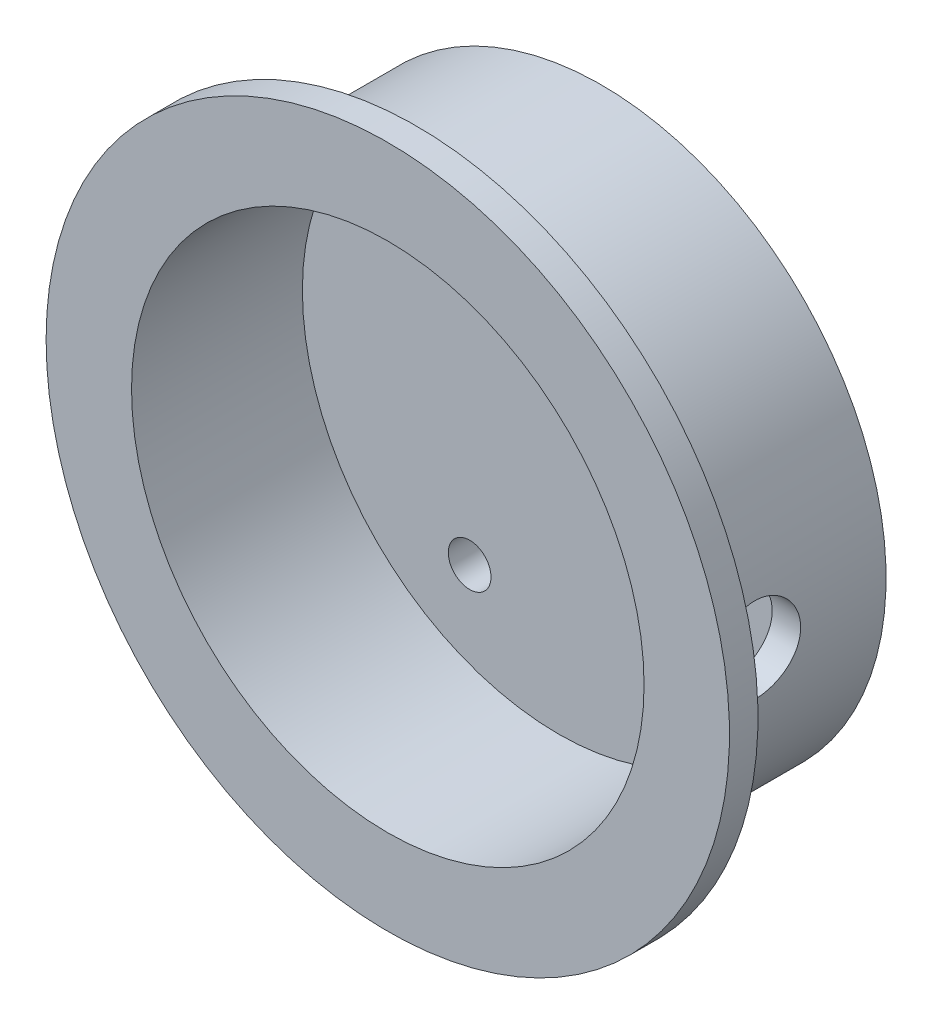
SolidWorks part; units mm, degrees
ref_plane "前视基准面" through (0, 0, 0) normal (0, 0, 1) x (1, 0, 0)
ref_plane "上视基准面" through (0, 0, 0) normal (0, 1, 0) x (1, 0, 0)
ref_plane "右视基准面" through (0, 0, 0) normal (1, 0, 0) x (0, 0, -1)
sketch "草图2" plane through (0, 0, 0) normal (0, 1, 0) x (1, 0, 0)
  line L0 (0, 0) -> (0, -1) construction
  line L1 (0, 0) -> (40, 0)
  line L2 (40, 0) -> (40, -26)
  line L3 (40, -26) -> (48, -26)
  line L4 (48, -26) -> (48, -30)
  line L5 (48, -30) -> (36, -30)
  line L6 (36, -30) -> (36, -6)
  line L7 (36, -6) -> (0, -6)
  line L8 (0, -6) -> (0, 0)
revolve "旋转2" add sketch "草图2" angle 360 about L0
sketch "草图3" plane through (0, 0, 0) normal (0, 0, 1) x (1, 0, 0)
  circle A0 centre (25, 0) radius 3
  circle A1 centre (-12.5, 21.6506) radius 3
  circle A2 centre (-12.5, -21.6506) radius 3
extrude "切除-拉伸1" cut sketch "草图3" along normal through all
ref_plane "基准面1" through (40, 0, 0) normal (1, 0, 0) x (0, 0, -1)
sketch "草图4" plane through (40, 0, 0) normal (1, 0, 0) x (0, 0, -1)
  circle A0 centre (-18, 0) radius 6
extrude "切除-拉伸2" cut sketch "草图4" against normal blind 6
